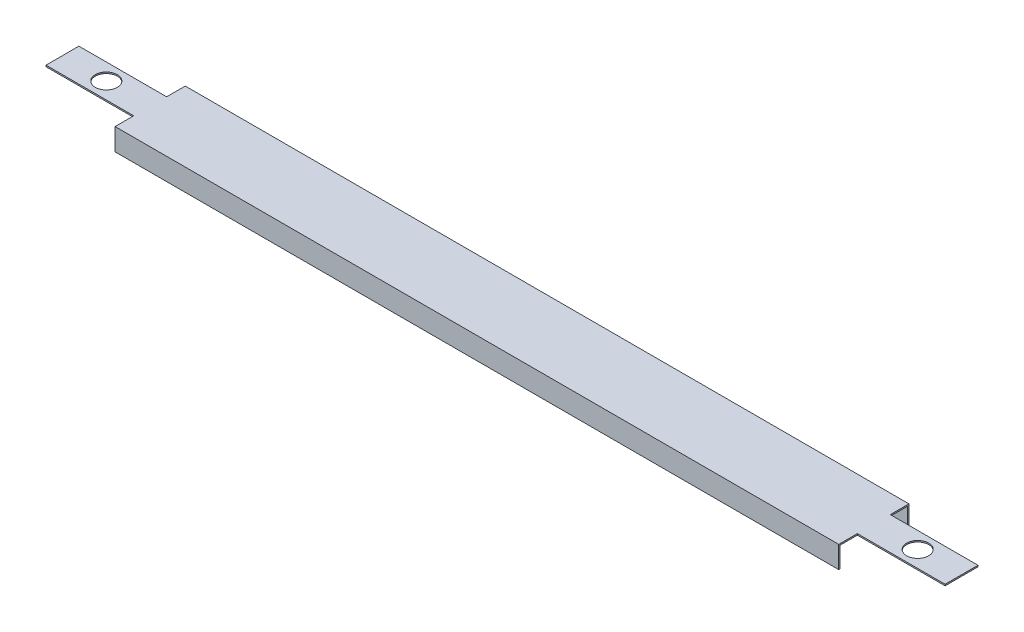
SolidWorks part; units mm, degrees
ref_plane "Front Plane" through (0, 0, 0) normal (0, 0, 1) x (1, 0, 0)
ref_plane "Top Plane" through (0, 0, 0) normal (0, 1, 0) x (1, 0, 0)
ref_plane "Right Plane" through (0, 0, 0) normal (1, 0, 0) x (0, 0, -1)
sketch "Sketch2" plane through (0, 0, 0) normal (0, 1, 0) x (1, 0, 0)
  line L0 (107.95, 0) -> (-107.95, 0) construction
  line L1 (-130.175, -10.16) -> (130.175, -10.16)
  line L2 (-130.175, -10.16) -> (-130.175, 10.16)
  line L3 (-130.175, 10.16) -> (130.175, 10.16)
  line L4 (130.175, -10.16) -> (130.175, 10.16)
  line L5 (-130.175, -10.16) -> (130.175, 10.16) construction
  line L6 (-130.175, 10.16) -> (130.175, -10.16) construction
  line L7 (-107.95, 10.16) -> (-107.95, -10.16) construction
  line L8 (-117.475, 0) -> (-107.95, 0) construction
  line L9 (107.95, 0) -> (117.475, 0) construction
  line L10 (107.95, -10.16) -> (107.95, 10.16) construction
  circle A0 centre (-117.475, 0) radius 3.1877
  circle A1 centre (117.475, 0) radius 3.1877
  point P0 (0, 0)
  point P9 (0, 0)
  point P17 (0, 0)
  point P19 (107.95, 0)
  dimension "D5" = 6.3754
  dimension "D1" = 20.32
  dimension "D2" = 12.7
  dimension "D3" = 215.9
  dimension "D4" = 9.525
extrude "Boss-Extrude1" add sketch "Sketch2" against normal blind 6.35
sketch "Sketch3" plane through (130.175, 0, 0) normal (1, 0, 0) x (0, 0, -1)
  line L5 (-9.7536, -6.35) -> (9.7536, -6.35)
  line L8 (9.7536, -0.4064) -> (9.7536, -6.35)
  line L9 (-9.7536, -0.4064) -> (9.7536, -0.4064)
  line L10 (-9.7536, -6.35) -> (-9.7536, -0.4064)
  line L11 (9.7536, -0.4064) -> (9.7536, -6.35)
  line L12 (-9.7536, -0.4064) -> (9.7536, -0.4064)
  line L13 (-9.7536, -6.35) -> (-9.7536, -0.4064)
  dimension "D1" = 0.4064
extrude "Cut-Extrude1" cut sketch "Sketch3" against normal through all
sketch "Sketch4" plane through (0, 0, 0) normal (0, 1, 0) x (1, 0, 0)
  line L1 (-130.175, 10.16) -> (-104.775, 10.16)
  line L2 (-130.175, 10.16) -> (-130.175, 4.7625)
  line L3 (-130.175, 4.7625) -> (-104.775, 4.7625)
  line L4 (-104.775, 10.16) -> (-104.775, 4.7625)
  line L5 (-130.175, -10.16) -> (-104.775, -10.16)
  line L6 (-130.175, -10.16) -> (-130.175, -4.7625)
  line L7 (-130.175, -4.7625) -> (-104.775, -4.7625)
  line L8 (-104.775, -10.16) -> (-104.775, -4.7625)
  line L9 (130.175, 10.16) -> (104.775, 10.16)
  line L10 (130.175, 10.16) -> (130.175, 4.7625)
  line L11 (130.175, 4.7625) -> (104.775, 4.7625)
  line L12 (104.775, 10.16) -> (104.775, 4.7625)
  line L13 (130.175, -10.16) -> (104.775, -10.16)
  line L14 (130.175, -10.16) -> (130.175, -4.7625)
  line L15 (130.175, -4.7625) -> (104.775, -4.7625)
  line L16 (104.775, -10.16) -> (104.775, -4.7625)
  dimension "D1" = 9.525
  dimension "D2" = 25.4
extrude "Cut-Extrude2" cut sketch "Sketch4" against normal through all
